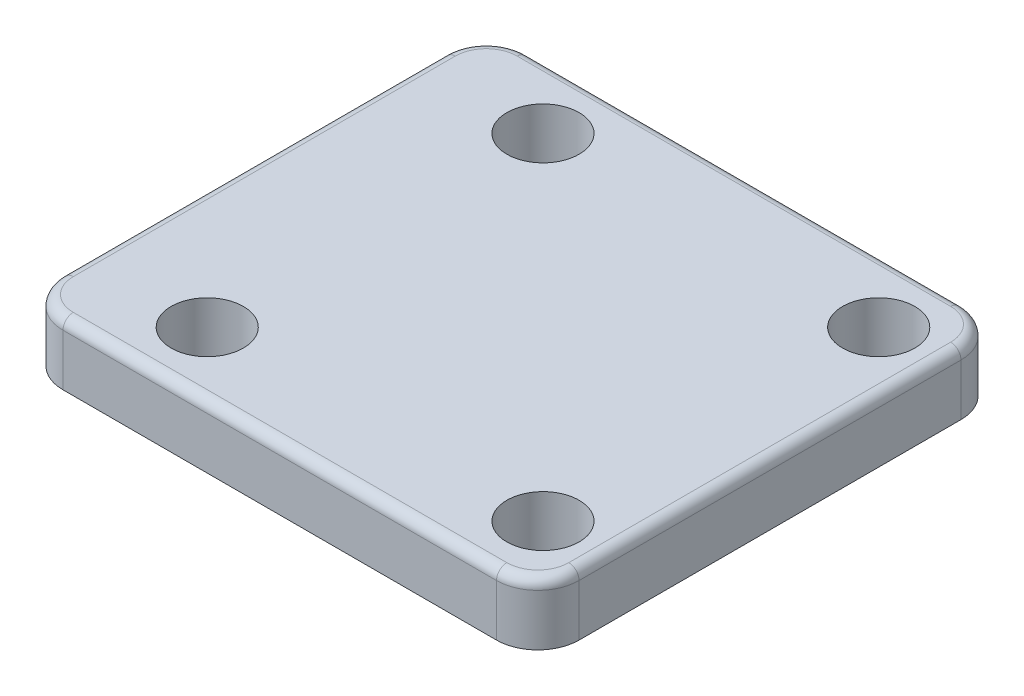
SolidWorks part; units mm, degrees
ref_plane "Front Plane" through (0, 0, 0) normal (0, 0, 1) x (1, 0, 0)
ref_plane "Top Plane" through (0, 0, 0) normal (0, 1, 0) x (1, 0, 0)
ref_plane "Right Plane" through (0, 0, 0) normal (1, 0, 0) x (0, 0, -1)
sketch "Sketch1" plane through (0, 0, 0) normal (0, 1, 0) x (1, 0, 0)
  line L1 (18, 22.5) -> (-24, 22.5)
  line L2 (22, 18.5) -> (22, -18.5)
  line L3 (18, -22.5) -> (-24, -22.5)
  line L4 (-28, 18.5) -> (-28, -18.5)
  arc A0 (-24, -22.5) -> (-28, -18.5) centre (-24, -18.5) cw
  arc A1 (22, -18.5) -> (18, -22.5) centre (18, -18.5) cw
  arc A2 (18, 22.5) -> (22, 18.5) centre (18, 18.5) cw
  arc A3 (-24, 22.5) -> (-28, 18.5) centre (-24, 18.5) ccw
  point P9 (22, -22.5)
  point P12 (22, 22.5)
  point P15 (-28, 22.5)
  dimension "D5" = 4
  dimension "D1" = 50
  dimension "D2" = 45
  dimension "D3" = 22
  dimension "D4" = 22.5
extrude "Boss-Extrude1" add sketch "Sketch1" along normal blind 6
ref_plane "Plane1" through (-3, 0, 0) normal (1, 0, 0) x (0, 0, -1)
sketch "Sketch3" plane through (0, 6, 0) normal (0, 1, 0) x (1, 0, 0)
  line L0 (0, 0) -> (23, 0) construction
  line L1 (0, 0) -> (16.2635, 16.2635) construction
  circle A0 centre (0, 0) radius 23
  circle A1 centre (16.2635, 16.2635) radius 3.5
  circle A2 centre (16.2635, -16.2635) radius 3.5
  circle A3 centre (-16.2635, -16.2635) radius 3.5
  circle A4 centre (-16.2635, 16.2635) radius 3.5
  point P15 (0, 0)
  dimension "D1" = 45
  dimension "D2" = 4
extrude "Cut-Extrude1" cut sketch "Sketch3" against normal through all contours A3 | A4 | A2 | A1
fillet "Fillet3" radius 1 8 edges at (-28, 6, 0) (-26.8284, 6, -21.3284) (-3, 6, -22.5) (20.8284, 6, -21.3284) (22, 6, 0) (20.8284, 6, 21.3284) (-26.8284, 6, 21.3284) (-3, 6, 22.5)
sketch "Sketch4" plane through (0, 0, 0) normal (0, -1, 0) x (-1, 0, 0)
  circle A0 centre (0, 0) radius 16
extrude "Boss-Extrude2" add sketch "Sketch4" along normal blind 2
chamfer "Chamfer1" distance 1 angle 45 1 edges at (0, -2, -16)
